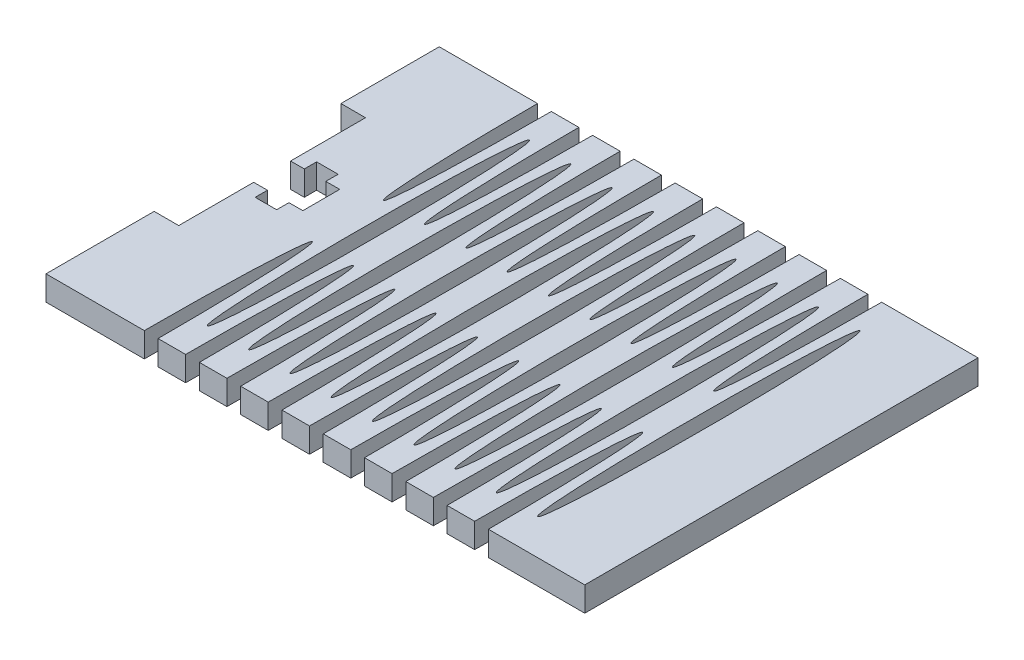
SolidWorks part; units mm, degrees
ref_plane "Front Plane" through (0, 0, 0) normal (0, 0, 1) x (1, 0, 0)
ref_plane "Top Plane" through (0, 0, 0) normal (0, 1, 0) x (1, 0, 0)
ref_plane "Right Plane" through (0, 0, 0) normal (1, 0, 0) x (0, 0, -1)
sketch "Sketch1" plane through (0, 0, 0) normal (0, 1, 0) x (1, 0, 0)
  line L0 (0, 13.97) -> (3.175, 13.97)
  line L1 (0, 0) -> (12.7, 0)
  line L2 (0, 0) -> (0, 13.97)
  line L3 (0, 50.8) -> (12.7, 50.8)
  line L4 (16.256, 46.1962) -> (16.256, 50.8) construction
  line L5 (3.175, 13.97) -> (3.175, 23.6537)
  line L6 (3.175, 38.1) -> (0, 38.1)
  line L7 (3.175, 23.6537) -> (4.953, 23.6538)
  line L8 (4.953, 23.6538) -> (4.953, 22.0662)
  line L9 (4.953, 22.0662) -> (7.7311, 22.0662)
  line L10 (7.7311, 22.0662) -> (7.7311, 23.6538)
  line L11 (7.7311, 23.6538) -> (9.525, 23.6538)
  line L12 (9.525, 23.6538) -> (9.525, 28.4163)
  line L13 (9.525, 28.4163) -> (7.7311, 28.4163)
  line L14 (7.7311, 28.4163) -> (7.7311, 30.0038)
  line L15 (7.7311, 30.0038) -> (4.953, 30.0038)
  line L16 (4.953, 30.0038) -> (4.953, 28.4163)
  line L17 (4.953, 28.4163) -> (3.175, 28.4163)
  line L18 (3.175, 28.4163) -> (3.175, 38.1)
  line L19 (0, 38.1) -> (0, 50.8)
  line L20 (13.589, 30.0038) -> (13.589, 20.7962) construction
  line L21 (13.589, 30.0038) -> (13.589, 50.8) construction
  line L22 (13.589, 20.7962) -> (13.589, 0) construction
  line L23 (14.478, 50.8) -> (18.034, 50.8)
  line L24 (19.812, 50.8) -> (23.368, 50.8)
  line L25 (23.368, 0) -> (19.812, 0)
  line L26 (25.146, 50.8) -> (28.702, 50.8)
  line L27 (18.034, 0) -> (14.478, 0)
  line L28 (28.702, 0) -> (25.146, 0)
  line L29 (30.48, 50.8) -> (34.036, 50.8)
  line L30 (12.7, 50.8) -> (13.589, 50.8) construction
  line L31 (13.589, 50.8) -> (14.478, 50.8) construction
  line L32 (12.7, 0) -> (13.589, 0) construction
  line L33 (13.589, 0) -> (14.478, 0) construction
  line L34 (34.036, 0) -> (30.48, 0)
  line L35 (35.814, 50.8) -> (39.37, 50.8)
  line L36 (39.37, 0) -> (35.814, 0)
  line L37 (41.148, 50.8) -> (44.704, 50.8)
  line L38 (44.704, 0) -> (41.148, 0)
  line L39 (46.482, 50.8) -> (50.038, 50.8)
  line L40 (50.038, 0) -> (46.482, 0)
  line L41 (51.816, 50.8) -> (55.372, 50.8)
  line L42 (55.372, 0) -> (51.816, 0)
  line L43 (57.15, 50.8) -> (60.706, 50.8)
  line L44 (60.706, 0) -> (57.15, 0)
  line L45 (60.706, 50.8) -> (69.596, 50.8)
  line L46 (69.596, 50.8) -> (69.596, 0)
  line L47 (69.596, 0) -> (60.706, 0)
  ellipse E0 centre (16.256, 25.4) end of major axis (16.256, 4.6037) minor radius 0.9525
  ellipse E1 centre (13.589, 50.8) end of major axis (13.589, 71.5962) minor radius 0.889 (14.478, 50.8) -> (12.7, 50.8) cw
  ellipse E2 centre (13.589, 0) end of major axis (13.589, 20.7962) minor radius 0.889 (14.478, 0) -> (12.7, 0) ccw
  ellipse E3 centre (18.923, 50.8) end of major axis (18.923, 71.5962) minor radius 0.889 (19.812, 50.8) -> (18.034, 50.8) cw
  ellipse E4 centre (21.59, 25.4) end of major axis (21.59, 4.6037) minor radius 0.9525
  ellipse E5 centre (18.923, 0) end of major axis (18.923, 20.7962) minor radius 0.889 (19.812, 0) -> (18.034, 0) ccw
  ellipse E6 centre (24.257, 50.8) end of major axis (24.257, 30.0038) minor radius 0.889 (25.146, 50.8) -> (23.368, 50.8) cw
  ellipse E7 centre (26.924, 25.4) end of major axis (26.924, 4.6037) minor radius 0.9525
  ellipse E8 centre (24.257, 0) end of major axis (24.257, 20.7962) minor radius 0.889 (25.146, 0) -> (23.368, 0) ccw
  ellipse E9 centre (29.591, 50.8) end of major axis (29.591, 30.0038) minor radius 0.889 (30.48, 50.8) -> (28.702, 50.8) cw
  ellipse E10 centre (32.258, 25.4) end of major axis (32.258, 4.6037) minor radius 0.9525
  ellipse E11 centre (29.591, 0) end of major axis (29.591, 20.7962) minor radius 0.889 (30.48, 0) -> (28.702, 0) ccw
  ellipse E12 centre (34.925, 50.8) end of major axis (34.925, 30.0038) minor radius 0.889 (35.814, 50.8) -> (34.036, 50.8) cw
  ellipse E13 centre (37.592, 25.4) end of major axis (37.592, 4.6037) minor radius 0.9525
  ellipse E14 centre (34.925, 0) end of major axis (34.925, 20.7962) minor radius 0.889 (35.814, 0) -> (34.036, 0) ccw
  ellipse E15 centre (40.259, 50.8) end of major axis (40.259, 30.0038) minor radius 0.889 (41.148, 50.8) -> (39.37, 50.8) cw
  ellipse E16 centre (42.926, 25.4) end of major axis (42.926, 4.6037) minor radius 0.9525
  ellipse E17 centre (40.259, 0) end of major axis (40.259, 20.7962) minor radius 0.889 (41.148, 0) -> (39.37, 0) ccw
  ellipse E18 centre (45.593, 50.8) end of major axis (45.593, 30.0038) minor radius 0.889 (46.482, 50.8) -> (44.704, 50.8) cw
  ellipse E19 centre (48.26, 25.4) end of major axis (48.26, 4.6037) minor radius 0.9525
  ellipse E20 centre (45.593, 0) end of major axis (45.593, 20.7962) minor radius 0.889 (46.482, 0) -> (44.704, 0) ccw
  ellipse E21 centre (50.927, 50.8) end of major axis (50.927, 71.5962) minor radius 0.889 (51.816, 50.8) -> (50.038, 50.8) cw
  ellipse E22 centre (53.594, 25.4) end of major axis (53.594, 4.6037) minor radius 0.9525
  ellipse E23 centre (50.927, 0) end of major axis (50.927, 20.7962) minor radius 0.889 (51.816, 0) -> (50.038, 0) ccw
  ellipse E24 centre (56.261, 50.8) end of major axis (56.261, 71.5962) minor radius 0.889 (57.15, 50.8) -> (55.372, 50.8) cw
  ellipse E25 centre (58.928, 25.4) end of major axis (58.928, 4.6037) minor radius 0.9525
  ellipse E26 centre (56.261, 0) end of major axis (56.261, 20.7962) minor radius 0.889 (57.15, 0) -> (55.372, 0) ccw
  dimension "D1" = 12.7
  dimension "D2" = 4.7625
  dimension "D3" = 24.13
  dimension "D4" = 7.9375
  dimension "D5" = 9.6837
  dimension "D6" = 9.525
  dimension "D7" = 50.8
  dimension "D8" = 12.7
  dimension "D9" = 3.175
  dimension "D10" = 2.7781
  dimension "D11" = 1.778
  dimension "D12" = 1.778
  dimension "D13" = 3.556
  dimension "D14" = 1.778
  dimension "D15" = 25.4
  dimension "D16" = 9
  dimension "D17" = 8.89
extrude "Boss-Extrude1" add sketch "Sketch1" along normal blind 3.175
equation "\"Plywood Thickness\"= 0.125"
equation "\"D9@Sketch1\"=\"Plywood Thickness\""
equation "\"D1@Boss-Extrude1\"=\"Plywood Thickness\""
